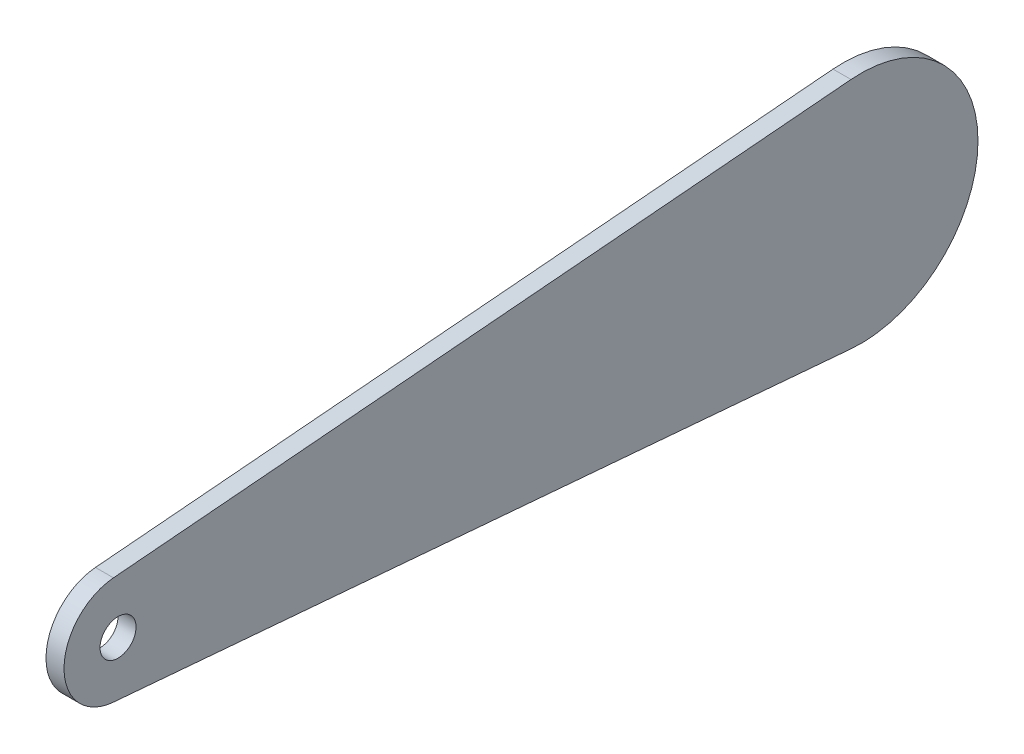
SolidWorks part; units mm, degrees
ref_plane "Front Plane" through (0, 0, 0) normal (0, 0, 1) x (1, 0, 0)
ref_plane "Top Plane" through (0, 0, 0) normal (0, 1, 0) x (1, 0, 0)
ref_plane "Right Plane" through (0, 0, 0) normal (1, 0, 0) x (0, 0, -1)
sketch "Sketch1" plane through (0, 0, 0) normal (1, 0, 0) x (0, 0, -1)
  line L1 (-208.7852, 29.8918) -> (200.7242, 64.7656)
  line L2 (-208.7852, -29.8918) -> (200.7242, -64.7656)
  arc A0 (-208.7852, 29.8918) -> (-208.7852, -29.8918) centre (-206.2396, 0) ccw
  arc A1 (200.7242, -64.7656) -> (200.7242, 64.7656) centre (206.2396, 0) ccw
  circle A2 centre (-206.2396, 0) radius 10
  point P4 (0, 0)
  dimension "D2" = 60
  dimension "D3" = 130
  dimension "D1" = 412.4792
extrude "Boss-Extrude3" add sketch "Sketch1" along normal blind 10
